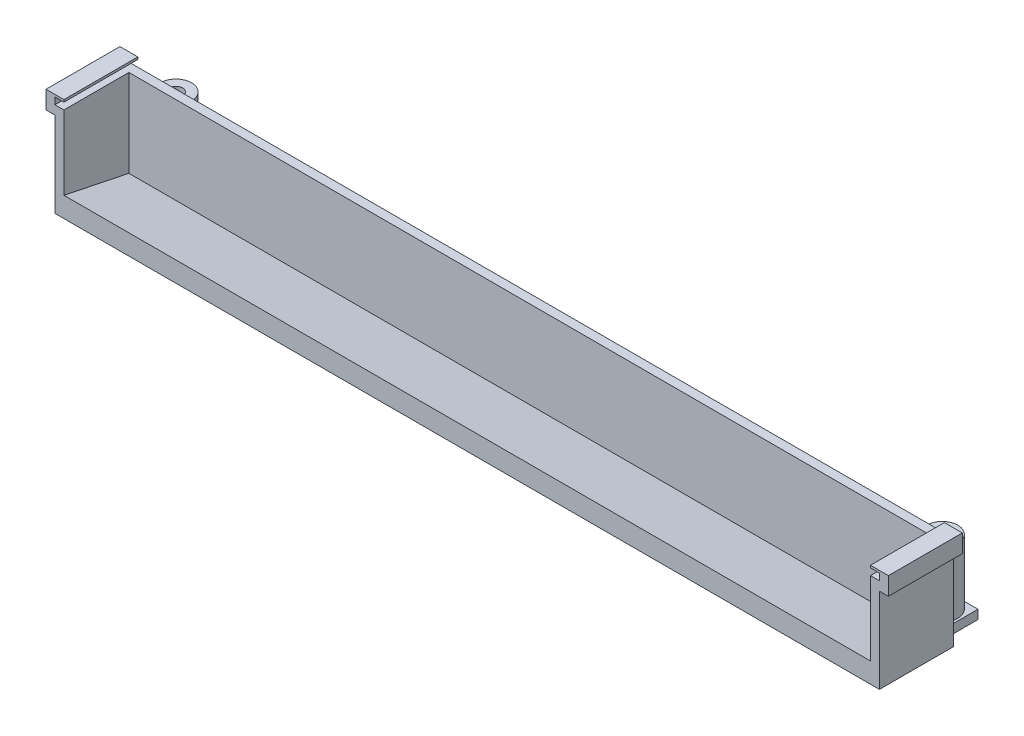
SolidWorks part; units mm, degrees
ref_plane "Ebene vorne" through (0, 0, 0) normal (0, 0, 1) x (1, 0, 0)
ref_plane "Ebene oben" through (0, 0, 0) normal (0, 1, 0) x (1, 0, 0)
ref_plane "Ebene rechts" through (0, 0, 0) normal (1, 0, 0) x (0, 0, -1)
sketch "Skizze1" plane through (0, 0, 0) normal (0, 1, 0) x (1, 0, 0)
  line L1 (-90, -7.25) -> (90, -7.25)
  line L2 (-90, -7.25) -> (-90, 7.25)
  line L3 (-90, 7.25) -> (90, 7.25)
  line L4 (90, -7.25) -> (90, 7.25)
  line L5 (-90, -7.25) -> (90, 7.25) construction
  line L6 (-90, 7.25) -> (90, -7.25) construction
  point P0 (0, 0)
  dimension "D1" = 180
  dimension "D2" = 14.5
extrude "Aufsatz-Linear austragen1" add sketch "Skizze1" along normal blind 4.5
sketch "Skizze2" plane through (-90, 0, 0) normal (-1, 0, 0) x (0, 0, 1)
  line L6 (-7.25, 4.5) -> (7.25, 4.5)
  line L7 (-7.25, 1.5) -> (7.25, 4.5)
  line L8 (-7.25, 4.5) -> (-7.25, 0) construction
  line L9 (55, 0) -> (-55, 0) construction
  line L10 (-7.25, 4.5) -> (-7.25, 1.5)
  dimension "D1" = 1.5
extrude "Schnitt-Linear austragen2" cut sketch "Skizze2" against normal through all contours L10 L7 L6
sketch "Skizze4" plane through (0, 0, 0) normal (0, 1, 0) x (1, 0, 0)
  line L1 (90, 7.25) -> (-90, 7.25)
  line L2 (90, 7.25) -> (90, 9.25)
  line L3 (90, 9.25) -> (-90, 9.25)
  line L4 (-90, 7.25) -> (-90, 9.25)
  line L5 (90, 7.25) -> (-90, 9.25) construction
  line L6 (90, 9.25) -> (-90, 7.25) construction
  line L7 (-90, 9.25) -> (-92, 9.25)
  line L8 (-90, 9.25) -> (-90, -7.25)
  line L9 (-90, -7.25) -> (-92, -7.25)
  line L10 (-92, 9.25) -> (-92, -7.25)
  line L11 (-90, 9.25) -> (-92, -7.25) construction
  line L12 (-90, -7.25) -> (-92, 9.25) construction
  line L13 (90, -7.25) -> (92, -7.25)
  line L14 (90, -7.25) -> (90, 9.25)
  line L15 (90, 9.25) -> (92, 9.25)
  line L16 (92, -7.25) -> (92, 9.25)
  line L17 (90, -7.25) -> (92, 9.25) construction
  line L18 (90, 9.25) -> (92, -7.25) construction
  line L23 (-90, -7.25) -> (90, -7.25) construction
  point P4 (0, 8.25)
  point P9 (-91, 1)
  point P13 (91, 1)
  point P15 (0, 0)
  point P16 (0, 0)
  dimension "D1" = 2
  dimension "D2" = 2
  dimension "D3" = 2
  dimension "D4" = 0
  dimension "D5" = 0
extrude "Aufsatz-Linear austragen2" add sketch "Skizze4" along normal blind 21 contours L4 L1 L2 L3 | L13 L16 L15 L2 L14 | L7 L10 L9 L8 L4
sketch "Skizze5" plane through (0, 0, 0) normal (0, 1, 0) x (1, 0, 0)
  line L0 (92, 9.25) -> (-92, 9.25) construction
  line L1 (-89.5, 9.25) -> (-81.5, 9.25)
  line L2 (-89.5, 9.25) -> (-89.5, 17.25)
  line L3 (-89.5, 17.25) -> (-81.5, 17.25)
  line L4 (-81.5, 9.25) -> (-81.5, 17.25)
  line L5 (-89.5, 9.25) -> (-81.5, 17.25) construction
  line L6 (-89.5, 17.25) -> (-81.5, 9.25) construction
  line L7 (-92, 9.25) -> (-92, -7.25) construction
  line L8 (89.5, 9.25) -> (81.5, 9.25)
  line L9 (89.5, 9.25) -> (89.5, 17.25)
  line L10 (89.5, 17.25) -> (81.5, 17.25)
  line L11 (81.5, 9.25) -> (81.5, 17.25)
  line L12 (89.5, 9.25) -> (81.5, 17.25) construction
  line L13 (89.5, 17.25) -> (81.5, 9.25) construction
  point P4 (-85.5, 13.25)
  point P11 (85.5, 13.25)
  dimension "D1" = 8
  dimension "D2" = 8
  dimension "D3" = 8
  dimension "D4" = 8
  dimension "D5" = 171
  dimension "D6" = 6.5
extrude "Aufsatz-Linear austragen3" add sketch "Skizze5" along normal blind 2
sketch "Skizze6" plane through (0, 2, 0) normal (0, 1, 0) x (1, 0, 0)
  line L0 (-81.5, 9.25) -> (-81.5, 17.25) construction
  line L1 (-81.5, 17.25) -> (-89.5, 17.25) construction
  line L2 (89.5, 9.25) -> (89.5, 17.25) construction
  line L4 (89.5, 17.25) -> (81.5, 17.25) construction
  circle A0 centre (-85.5, 13.25) radius 3.5
  circle A1 centre (85.5, 13.25) radius 3.5
  dimension "D1" = 7
  dimension "D6" = 7
  dimension "D2" = 4
  dimension "D3" = 4
  dimension "D4" = 4
  dimension "D5" = 4
extrude "Aufsatz-Linear austragen4" add sketch "Skizze6" along normal blind 14.5
sketch "Skizze7" plane through (0, 16.5, 0) normal (0, 1, 0) x (1, 0, 0)
  line L0 (89.5, 9.25) -> (89.5, 17.25) construction
  line L1 (89.5, 17.25) -> (81.5, 17.25) construction
  circle A0 centre (85.5, 13.25) radius 1.5
  circle A2 centre (-85.5, 13.25) radius 1.5
  dimension "D3" = 3
  dimension "D4" = 3
  dimension "D1" = 4
  dimension "D2" = 4
extrude "Schnitt-Linear austragen3" cut sketch "Skizze7" against normal blind 10
sketch "Skizze8" plane through (92, 0, 0) normal (1, 0, 0) x (0, 0, -1)
  line L0 (9.25, 21) -> (9.25, 0) construction
  line L1 (-7.25, 21) -> (9.25, 21)
  line L2 (-7.25, 21) -> (-7.25, 19)
  line L3 (-7.25, 19) -> (9.25, 19)
  line L4 (9.25, 21) -> (9.25, 19)
  dimension "D1" = 2
extrude "Aufsatz-Linear austragen5" add sketch "Skizze8" along normal blind 2
sketch "Skizze9" plane through (0, 21, 0) normal (0, 1, 0) x (1, 0, 0)
  line L0 (90, -7.25) -> (94, -7.25) construction
  line L1 (94, 9.25) -> (92, 9.25)
  line L2 (94, 9.25) -> (94, -7.25)
  line L3 (94, -7.25) -> (92, -7.25)
  line L4 (92, 9.25) -> (92, -7.25)
extrude "Aufsatz-Linear austragen6" add sketch "Skizze9" along normal blind 2
sketch "Skizze10" plane through (92, 0, 0) normal (-1, 0, 0) x (0, 0, 1)
  line L0 (7.25, 23) -> (7.25, 21) construction
  line L1 (-9.25, 23) -> (7.25, 23)
  line L2 (-9.25, 23) -> (-9.25, 22.5)
  line L3 (-9.25, 22.5) -> (7.25, 22.5)
  line L4 (7.25, 23) -> (7.25, 22.5)
  dimension "D1" = 0.5
extrude "Aufsatz-Linear austragen7" add sketch "Skizze10" along normal blind 2
sketch "Skizze11" plane through (-92, 0, 0) normal (-1, 0, 0) x (0, 0, 1)
  line L1 (-9.25, 21) -> (7.25, 21)
  line L2 (-9.25, 21) -> (-9.25, 19)
  line L3 (-9.25, 19) -> (7.25, 19)
  line L4 (7.25, 21) -> (7.25, 19)
extrude "Aufsatz-Linear austragen8" add sketch "Skizze11" along normal blind 2
sketch "Skizze12" plane through (0, 21, 0) normal (0, 1, 0) x (1, 0, 0)
  line L0 (-90, -7.25) -> (-94, -7.25) construction
  line L1 (-94, 9.25) -> (-92, 9.25)
  line L2 (-94, 9.25) -> (-94, -7.25)
  line L3 (-94, -7.25) -> (-92, -7.25)
  line L4 (-92, 9.25) -> (-92, -7.25)
extrude "Aufsatz-Linear austragen9" add sketch "Skizze12" along normal blind 2
sketch "Skizze13" plane through (-92, 0, 0) normal (1, 0, 0) x (0, 0, -1)
  line L0 (-7.25, 23) -> (-7.25, 21) construction
  line L1 (9.25, 23) -> (-7.25, 23)
  line L2 (9.25, 23) -> (9.25, 22.5017)
  line L3 (9.25, 22.5017) -> (-7.25, 22.5017)
  line L4 (-7.25, 23) -> (-7.25, 22.5017)
extrude "Aufsatz-Linear austragen10" add sketch "Skizze13" along normal blind 2
